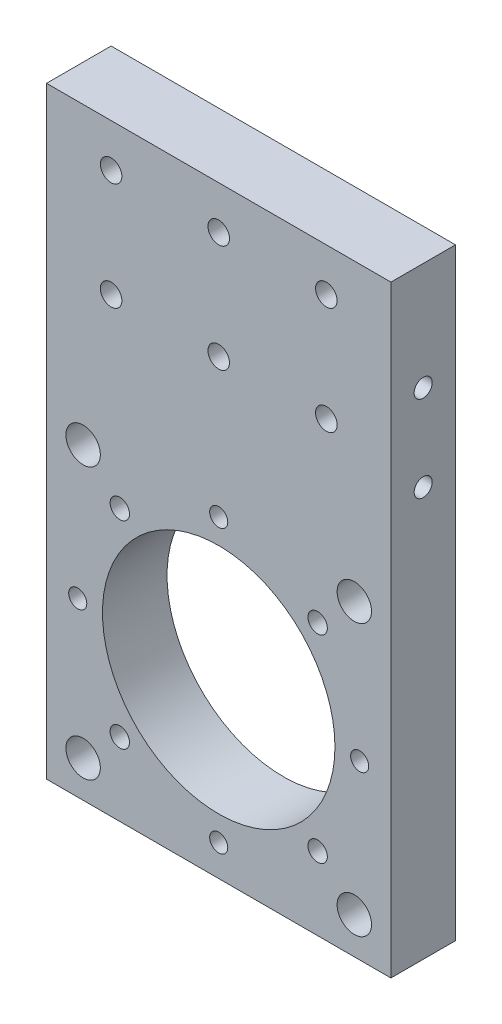
SolidWorks part; units mm, degrees
ref_plane "Front" through (0, 0, 0) normal (0, 0, 1) x (1, 0, 0)
ref_plane "Top" through (0, 0, 0) normal (0, 1, 0) x (1, 0, 0)
ref_plane "Right" through (0, 0, 0) normal (1, 0, 0) x (0, 0, -1)
sketch "Esquisse1" plane through (0, 0, 0) normal (0, 0, 1) x (1, 0, 0)
  line L0 (-40, 40) -> (40, 40)
  line L1 (-40, 40) -> (-40, -40)
  line L2 (40, 40) -> (40, -40)
  line L3 (-40, -40) -> (40, -40)
  line L12 (-40, 40) -> (40, -40) construction
  circle A18 centre (0, 0) radius 27
  dimension "D3" = 54
  dimension "D2" = 80
extrude "Boss.-Extru.1" add sketch "Esquisse1" along normal blind 15
sketch "Esquisse4" plane through (0, 0, 15) normal (0, 0, 1) x (1, 0, 0)
  line L0 (-40, 40) -> (40, -40) construction
  line L1 (-22.981, 22.981) -> (22.981, 22.981) construction
  line L2 (-22.981, 22.981) -> (-22.981, -22.981) construction
  line L3 (22.981, 22.981) -> (22.981, -22.981) construction
  line L4 (-22.981, -22.981) -> (22.981, -22.981) construction
  line L5 (0, 22.981) -> (0, 0) construction
  line L6 (-31.5, 31.5) -> (31.5, 31.5) construction
  line L7 (-31.5, 31.5) -> (-31.5, -31.5) construction
  line L8 (31.5, 31.5) -> (31.5, -31.5) construction
  line L9 (-31.5, -31.5) -> (31.5, -31.5) construction
  line L10 (0, 22.981) -> (0, 31.5) construction
  circle A3 centre (0, 0) radius 32.5 construction
  point P4 (0, 0)
  dimension "D1" = 65
  dimension "D2" = 63
hole_wizard "Chambrage pour vis à tête cylindrique à 6 pans creux (ou vis CHC) M41" positions "Esquisse3D6" profile "Esquisse16" counterbore size "M4" standard "Ansi Metric" end condition through all
sketch3d "Esquisse3D6"
  point P0 (31.5, 31.5, 15)
sketch "Esquisse16" plane through (31.5, 31.5, 15) normal (1, 0, 0) x (0, -1, 0)
  line L0 (0, 0) -> (0, 15)
  line L1 (0, 15) -> (2.25, 15)
  line L3 (2.25, 15) -> (2.25, 7)
  line L4 (2.25, 7) -> (4, 7)
  line L5 (4, 7) -> (4, 0)
  line L7 (4, 0) -> (0, 0)
  line L11 (0, -6.35) -> (0, 107.95) construction
  dimension "Diamètre du perçage jusqu'au prochain" = 4.5
  dimension "Profondeur du perçage jusqu'au prochain" = 15
  dimension "Diamètre du chambrage" = 8
  dimension "Profondeur du chambrage" = 7
sketch "Esquisse17" plane through (0, 0, 0) normal (0, 0, -1) x (-1, 0, 0)
  point P0 (-22.981, 22.981)
  point P1 (0, 0)
hole_wizard "Chambrage pour vis à tête cylindrique à 6 pans creux (ou vis CHC) M42" positions "Esquisse3D7" profile "Esquisse18" counterbore size "M4" standard "Ansi Metric" end condition through all
sketch3d "Esquisse3D7"
  point P0 (22.981, 22.981, 0)
sketch "Esquisse18" plane through (22.981, 22.981, 0) normal (1, 0, 0) x (0, 1, 0)
  line L0 (0, 0) -> (0, 15)
  line L1 (0, 15) -> (2.25, 15)
  line L3 (2.25, 15) -> (2.25, 7)
  line L4 (2.25, 7) -> (4, 7)
  line L5 (4, 7) -> (4, 0)
  line L7 (4, 0) -> (0, 0)
  line L11 (0, -6.35) -> (0, 107.95) construction
  dimension "Diamètre du perçage jusqu'au prochain" = 4.5
  dimension "Profondeur du perçage jusqu'au prochain" = 15
  dimension "Diamètre du chambrage" = 8
  dimension "Profondeur du chambrage" = 7
pattern_circular "Répétition circulaire3" count 4 over 360 about axis through (0, 0, 0) along (0, 0, 1) of "Chambrage pour vis à tête cylindrique à 6 pans creux (ou vis CHC) M41", "Chambrage pour vis à tête cylindrique à 6 pans creux (ou vis CHC) M42"
sketch "Esquisse2" plane through (0, 0, 15) normal (0, 0, 1) x (1, 0, 0)
  line L0 (-40, 40) -> (40, 40)
  line L1 (-40, 40) -> (-40, 100)
  line L2 (40, 40) -> (40, 100)
  line L3 (-40, 100) -> (40, 100)
  line L4 (40, 40) -> (-40, 40) construction
  dimension "D1" = 60
extrude "Boss.-Extru.2" add sketch "Esquisse2" against normal blind 15
sketch "Esquisse3" plane through (0, 0, 15) normal (0, 0, 1) x (1, 0, 0)
  line L0 (-40, 92.5) -> (40, 92.5) construction
  line L3 (0, 92.5) -> (0, 100) construction
  line L4 (40, 100) -> (-40, 100) construction
  line L5 (40, -40) -> (40, 100) construction
  line L6 (-40, 100) -> (-40, -40) construction
  circle A0 centre (-25, 92.5) radius 3.25
  circle A1 centre (25, 92.5) radius 3.25
  dimension "D1" = 6.5
  dimension "D2" = 50
  dimension "D3" = 7.5
extrude "Enlèv. mat.-Extru.1" [suppressed] cut sketch "Esquisse3" against normal through all
sketch "Esquisse7" plane through (40, 0, 0) normal (1, 0, 0) x (0, 0, -1)
  line L0 (-7.5, 100) -> (-7.5, 55) construction
  line L1 (0, 100) -> (-15, 100) construction
  point P4 (-7.5, 75)
  dimension "D2" = 45
  dimension "D1" = 20
hole_wizard "Trou taraudé profond M5x0.81" positions "Esquisse3D1" profile "Esquisse10" tap size "M5x0.8" standard "HASCO Metric"
sketch3d "Esquisse3D1"
  point P0 (40, 55, 7.5)
  point P3 (40, 75, 7.5)
sketch "Esquisse10" plane through (40, 55, 7.5) normal (0, 1, 0) x (0, 0, -1)
  line L0 (0, 0) -> (0, 23.6618)
  line L1 (0, 23.6618) -> (2.1, 22.4)
  line L2 (2.1, 22.4) -> (2.1, 0)
  line L5 (2.1, 0) -> (0, 0)
  line L10 (0, 23.6618) -> (-2.1, 22.4) construction
  line L11 (0, -6.35) -> (0, 107.95) construction
  dimension "Diamètre du trou pour taraudage" = 4.2
  dimension "Profondeur du trou pour taraudage" = 22.4
  dimension "Angle de pointe" = 118
cosmetic thread "Filetage de perçage21" parameters "D1"=20, "D2"=5
cosmetic thread "Filetage de perçage22" parameters "D1"=20, "D2"=5
mirror "Symétrie1" about plane through (0, 0, 0) normal (1, 0, 0) of "Trou taraudé profond M5x0.81"
cosmetic thread "Filetage de perçage23" parameters "D1"=20, "D2"=5
cosmetic thread "Filetage de perçage24" parameters "D1"=20, "D2"=5
sketch "Esquisse11" plane through (0, 0, 15) normal (0, 0, 1) x (1, 0, 0)
  line L0 (-40, 90) -> (40, 90) construction
  line L1 (-40, 100) -> (-40, -40) construction
  line L2 (40, -40) -> (40, 100) construction
  line L3 (0, 90) -> (0, 100) construction
  line L4 (40, 100) -> (-40, 100) construction
  point P6 (-25, 90)
  point P7 (25, 90)
  dimension "D1" = 25
  dimension "D2" = 10
hole_wizard "Trou taraudé M6x1.01" positions "Esquisse3D2" profile "Esquisse12" tap size "M6x1.0" standard "HASCO Metric" end condition through all
sketch3d "Esquisse3D2"
  point P0 (-25, 90, 15)
  point P3 (0, 90, 15)
  point P6 (25, 90, 15)
cosmetic thread "Filetage de perçage11" parameters "D2"=6
cosmetic thread "Filetage de perçage12" parameters "D2"=6
cosmetic thread "Filetage de perçage13" parameters "D2"=6
sketch "Esquisse12" plane through (-25, 90, 15) normal (1, 0, 0) x (0, -1, 0)
  line L0 (0, 0) -> (0, 15)
  line L1 (0, 15) -> (2.5, 15)
  line L2 (2.5, 15) -> (2.5, 0)
  line L5 (2.5, 0) -> (0, 0)
  line L11 (0, -6.35) -> (0, 107.95) construction
  dimension "Diamètre du trou pour taraudage jusqu'au prochain" = 5
  dimension "Profondeur du trou pour taraudage jusqu'au prochain" = 15
pattern_linear "Répétition linéaire1" count 2 spacing 25 along (0, -1, 0) of "Trou taraudé M6x1.01"
cosmetic thread "Filetage de perçage14" parameters "D2"=6
cosmetic thread "Filetage de perçage15" parameters "D2"=6
cosmetic thread "Filetage de perçage16" parameters "D2"=6
sketch "Esquisse13" plane through (0, 0, 15) normal (0, 0, 1) x (1, 0, 0)
  line L0 (0, 0) -> (-32.75, 0) construction
  dimension "D1" = 32.75
hole_wizard "Trou taraudé M5x0.81" positions "Esquisse3D4" profile "Esquisse14" tap size "M5x0.8" standard "Ansi Metric" end condition through all
sketch3d "Esquisse3D4"
  point P0 (-32.75, 0, 15)
sketch "Esquisse14" plane through (-32.75, 0, 15) normal (1, 0, 0) x (0, -1, 0)
  line L0 (0, 0) -> (0, 15)
  line L1 (0, 15) -> (2.1, 15)
  line L2 (2.1, 15) -> (2.1, 0)
  line L5 (2.1, 0) -> (0, 0)
  line L11 (0, -6.35) -> (0, 107.95) construction
  dimension "Diamètre du trou pour taraudage jusqu'au prochain" = 4.2
  dimension "Profondeur du trou pour taraudage jusqu'au prochain" = 15
cosmetic thread "Filetage de perçage25" parameters "D2"=5
pattern_circular "Répétition circulaire2" count 4 every 90 about axis through (0, 0, 0) along (0, 0, 1) of "Trou taraudé M5x0.81"
cosmetic thread "Filetage de perçage26" parameters "D2"=5
cosmetic thread "Filetage de perçage27" parameters "D2"=5
cosmetic thread "Filetage de perçage28" parameters "D2"=5
